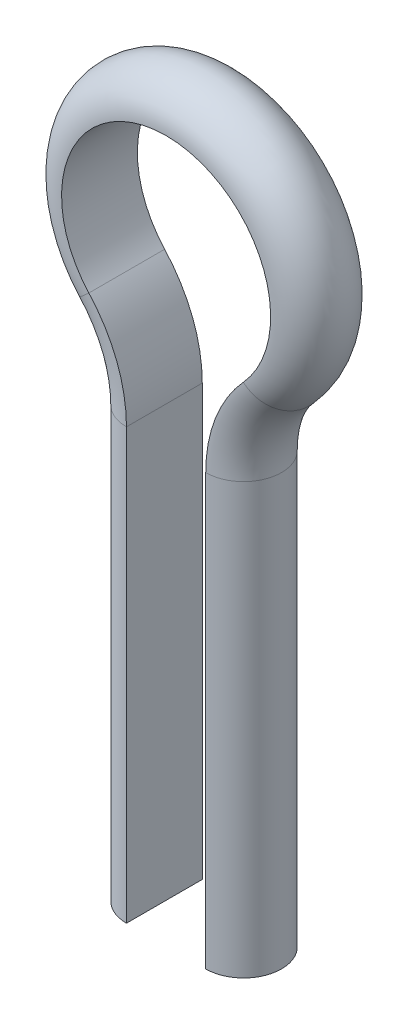
SolidWorks part; units mm, degrees
ref_plane "Front Plane" through (0, 0, 0) normal (0, 0, 1) x (1, 0, 0)
ref_plane "Top Plane" through (0, 0, 0) normal (0, 1, 0) x (1, 0, 0)
ref_plane "Right Plane" through (0, 0, 0) normal (1, 0, 0) x (0, 0, -1)
sketch "Sketch1" plane through (0, 0, 0) normal (0, 0, 1) x (1, 0, 0)
  line L0 (0, 0) -> (0, 58.712)
  line L1 (-10.0939, 100.5468) -> (-10.0939, -9.0405) construction
  line L2 (-20.1878, 0) -> (-20.1878, 58.712)
  arc A0 (3.9152, 68.8178) -> (-24.103, 68.8178) centre (-10.0939, 81.5896) ccw
  arc A1 (0, 58.712) -> (3.9152, 68.8178) centre (15, 58.712) cw
  arc A2 (-20.1878, 58.712) -> (-24.103, 68.8178) centre (-35.1878, 58.712) ccw
  dimension "D1" = 15
sketch "Sketch6" plane through (0, 0, 0) normal (0, 1, 0) x (1, 0, 0)
  line L0 (-4.6821, 5.2941) -> (-4.6821, -5.0588)
  arc A0 (-4.6821, -5.0588) -> (-4.6821, 5.2941) centre (-4.6821, 0.1176) ccw
sweep "Sweep3" add profiles "Sketch6" path "Sketch1"
